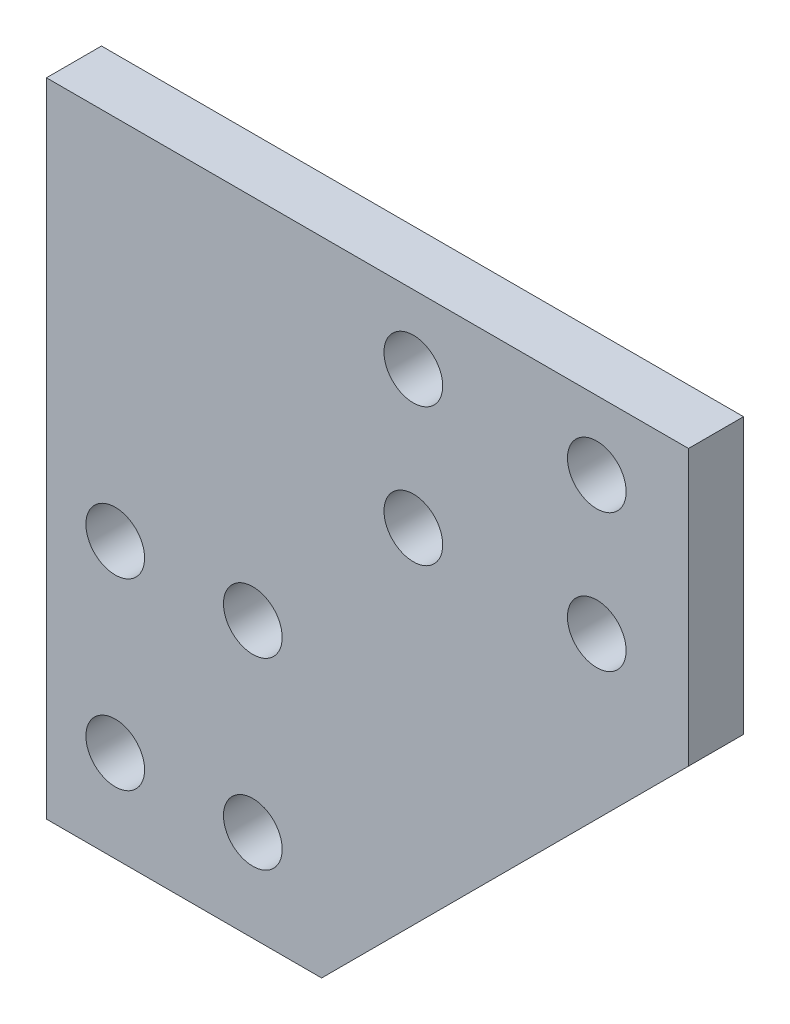
SolidWorks part; units mm, degrees
ref_plane "前视基准面" through (0, 0, 0) normal (0, 0, 1) x (1, 0, 0)
ref_plane "上视基准面" through (0, 0, 0) normal (0, 1, 0) x (1, 0, 0)
ref_plane "右视基准面" through (0, 0, 0) normal (1, 0, 0) x (0, 0, -1)
other "Configuration Table"
sketch "草图1" plane through (0, 0, 0) normal (0, 0, 1) x (1, 0, 0)
  line L0 (0, 0) -> (35, 0)
  line L1 (35, 0) -> (35, -15)
  line L2 (35, -15) -> (15, -35)
  line L3 (15, -35) -> (0, -35)
  line L4 (0, -35) -> (0, 0)
  line L5 (35, -7.5) -> (0, -7.5) construction
  line L6 (7.5, -35) -> (7.5, 0) construction
  line L7 (0, -25) -> (25, -25) construction
  line L8 (25, 0) -> (25, -25) construction
  circle A0 centre (3.75, -30) radius 1.6
  circle A1 centre (11.25, -30) radius 1.6
  circle A2 centre (11.25, -20) radius 1.6
  circle A3 centre (3.75, -20) radius 1.6
  circle A4 centre (30, -3.75) radius 1.6
  circle A5 centre (30, -11.25) radius 1.6
  circle A6 centre (20, -11.25) radius 1.6
  circle A7 centre (20, -3.75) radius 1.6
  dimension "D5" = 3.2
  dimension "D9" = 3.2
  dimension "D1" = 15
  dimension "D2" = 15
  dimension "D3" = 35
  dimension "D4" = 35
  dimension "D6" = 3.75
  dimension "D7" = 10
  dimension "D8" = 5
  dimension "D10" = 3.75
  dimension "D11" = 10
  dimension "D12" = 5
extrude "凸台-拉伸1" add sketch "草图1" along normal blind 3
